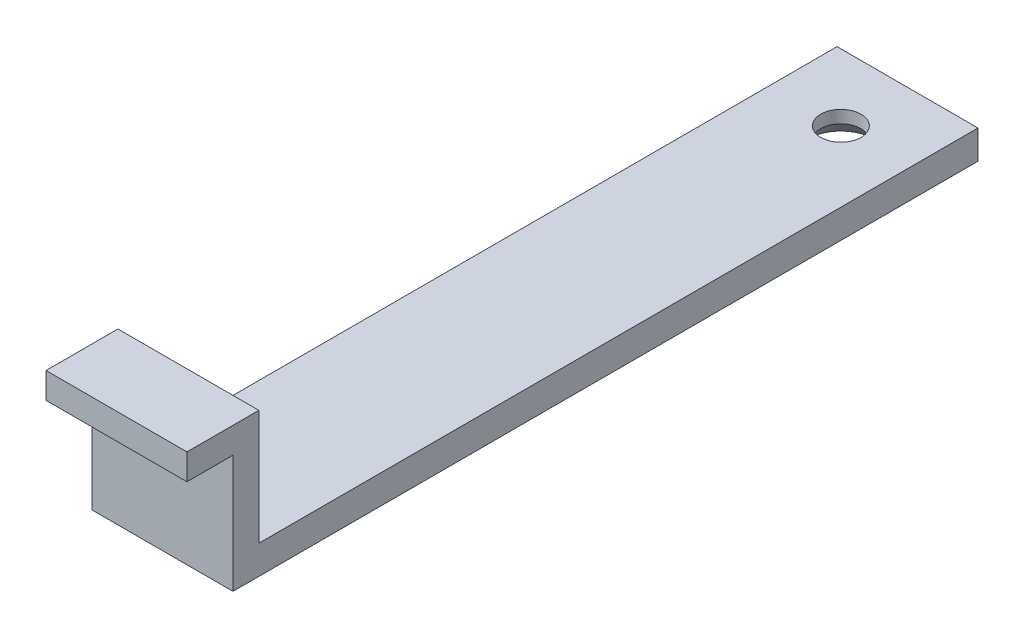
SolidWorks part; units mm, degrees
material "Nickel"
ref_plane "Front Plane" through (0, 0, 0) normal (0, 0, 1) x (1, 0, 0)
ref_plane "Top Plane" through (0, 0, 0) normal (0, 1, 0) x (1, 0, 0)
ref_plane "Right Plane" through (0, 0, 0) normal (1, 0, 0) x (0, 0, -1)
sketch "Sketch1" plane through (0, 0, 0) normal (0, 1, 0) x (1, 0, 0)
  line L1 (-3.1115, 0.5715) -> (3.1115, 0.5715)
  line L2 (-3.1115, 0.5715) -> (-3.1115, -0.5715)
  line L3 (-3.1115, -0.5715) -> (3.1115, -0.5715)
  line L4 (3.1115, 0.5715) -> (3.1115, -0.5715)
  line L5 (-3.1115, 0.5715) -> (3.1115, -0.5715) construction
  line L6 (-3.1115, -0.5715) -> (3.1115, 0.5715) construction
  point P0 (0, 0)
  dimension "D1" = 6.223
  dimension "D2" = 1.143
extrude "Boss-Extrude1" add sketch "Sketch1" along normal mid plane 6.35
sketch "Sketch2" plane through (0, 0, 0.5715) normal (0, 0, 1) x (1, 0, 0)
  line L0 (3.1115, 3.175) -> (3.1115, -3.175) construction
  line L1 (-3.1115, 3.175) -> (3.1115, 3.175)
  line L2 (-3.1115, 3.175) -> (-3.1115, 2.032)
  line L3 (-3.1115, 2.032) -> (3.1115, 2.032)
  line L4 (3.1115, 3.175) -> (3.1115, 2.032)
  dimension "D1" = 1.143
extrude "Boss-Extrude2" add sketch "Sketch2" along normal blind 2.032
sketch "Sketch3" plane through (0, 0, -0.5715) normal (0, 0, -1) x (-1, 0, 0)
  line L0 (3.1115, 3.175) -> (3.1115, -3.175) construction
  line L1 (-3.1115, -3.175) -> (3.1115, -3.175)
  line L2 (-3.1115, -3.175) -> (-3.1115, -1.905)
  line L3 (-3.1115, -1.905) -> (3.1115, -1.905)
  line L4 (3.1115, -3.175) -> (3.1115, -1.905)
  dimension "D1" = 1.27
extrude "Boss-Extrude3" add sketch "Sketch3" along normal blind 31.75
hole_wizard "CSK for #0 Flat Head Machine Screw1" positions "Sketch4" profile "Sketch5" countersink size "#0" standard "ANSI Inch"
sketch "Sketch4" plane through (0, -3.175, 0) normal (0, -1, 0) x (-1, 0, 0)
  point P0 (0, 29.378)
sketch "Sketch5" plane through (0, -3.175, -29.378) normal (1, 0, 0) x (0, 0, -1)
  line L0 (0, 0) -> (0, 5.1062)
  line L1 (0, 5.1062) -> (0.889, 4.572)
  line L2 (0.889, 4.572) -> (0.889, 0.7159)
  line L3 (0.889, 0.7159) -> (1.5113, 0)
  line L5 (1.5113, 0) -> (0, 0)
  line L6 (-0.889, 0.7159) -> (-1.5113, 0) construction
  line L10 (0, 5.1062) -> (-0.889, 4.572) construction
  line L11 (0, -6.35) -> (0, 107.95) construction
  dimension "Hole Dia." = 1.778
  dimension "Hole Depth" = 4.572
  dimension "Near C'Sink Dia." = 3.0226
  dimension "Near C'Sink Angle" = 82
  dimension "Drill Angle" = 118
